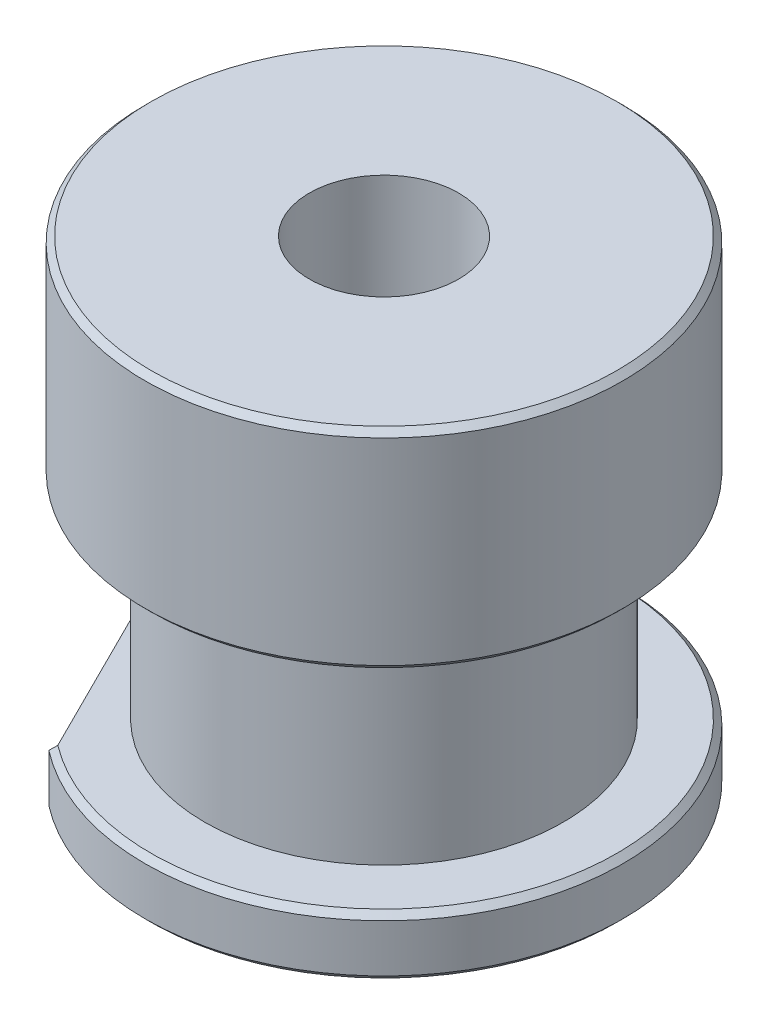
SolidWorks part; units mm, degrees
ref_plane "Piano frontale" through (0, 0, 0) normal (0, 0, 1) x (1, 0, 0)
ref_plane "Piano superiore" through (0, 0, 0) normal (0, 1, 0) x (1, 0, 0)
ref_plane "Piano destro" through (0, 0, 0) normal (1, 0, 0) x (0, 0, -1)
sketch "Sketch1" plane through (0, 0, 0) normal (0, 1, 0) x (1, 0, 0)
  circle A0 centre (0, 0) radius 8
extrude "Boss-Extrude1" add sketch "Sketch1" along normal blind 7
sketch "Sketch2" plane through (0, 7, 0) normal (0, 1, 0) x (1, 0, 0)
  circle A0 centre (0, 0) radius 6
extrude "Boss-Extrude2" add sketch "Sketch2" along normal blind 7
sketch "Sketch3" plane through (0, 14, 0) normal (0, 1, 0) x (1, 0, 0)
  circle A0 centre (0, 0) radius 8
extrude "Boss-Extrude3" add sketch "Sketch3" along normal blind 2
chamfer "Chamfer1" distance 0.2 4 edges at (0, 0, 8) (0, 7, 8) (0, 14, 8) (0, 16, 8)
sketch "Sketch4" plane through (0, 16, 0) normal (0, 1, 0) x (1, 0, 0)
  circle A0 centre (0, 0) radius 2.5
extrude "Cut-Extrude1" cut sketch "Sketch4" against normal blind 20
move or copy body "Body-Move/Copy1" bodies to move or copy 104 copy no rotation origin (0, 8, 0) rotation axis (1, 0, 0) rotation angle 180
sketch "Sketch5" plane through (0, 0, 0) normal (0, -1, 0) x (1, 0, 0)
  line L0 (-4.6928, 6.2304) -> (-7.8, 0)
  circle A0 centre (0, 0) radius 7.8 construction
  arc A1 (-4.6928, 6.2304) -> (-7.8, 0) centre (-6.2464, 3.1152) ccw
extrude "Cut-Extrude2" cut sketch "Sketch5" against normal blind 3
